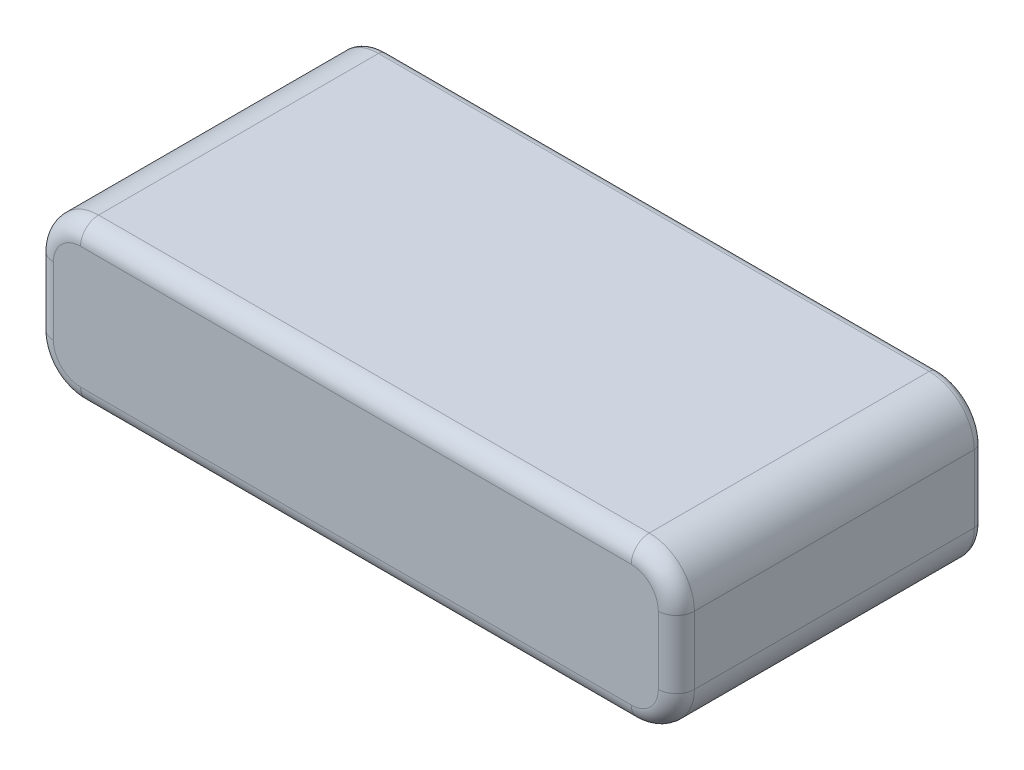
SolidWorks part; units mm, degrees
ref_plane "Front Plane" through (0, 0, 0) normal (0, 0, 1) x (1, 0, 0)
ref_plane "Top Plane" through (0, 0, 0) normal (0, 1, 0) x (1, 0, 0)
ref_plane "Right Plane" through (0, 0, 0) normal (1, 0, 0) x (0, 0, -1)
sketch "Sketch1" plane through (0, 0, 0) normal (0, 1, 0) x (1, 0, 0)
  line L1 (35.5, -17) -> (-35.5, -17)
  line L2 (35.5, -17) -> (35.5, 17)
  line L3 (35.5, 17) -> (-35.5, 17)
  line L4 (-35.5, -17) -> (-35.5, 17)
  line L5 (35.5, -17) -> (-35.5, 17) construction
  line L6 (35.5, 17) -> (-35.5, -17) construction
  point P0 (0, 0)
  dimension "D1" = 71
  dimension "D2" = 34
extrude "Boss-Extrude1" add sketch "Sketch1" along normal blind 17.5
fillet "Fillet1" radius 5 4 edges at (-35.5, 0, 0) (35.5, 0, 0) (35.5, 17.5, 0) (-35.5, 17.5, 0)
fillet "Fillet2" radius 2 8 edges at (-34.0355, 16.0355, 17) (0, 17.5, 17) (34.0355, 16.0355, 17) (35.5, 8.75, 17) (34.0355, 1.4645, 17) (0, 0, 17) (-34.0355, 1.4645, 17) (-35.5, 8.75, 17)
fillet "Fillet3" radius 1 8 edges at (34.0355, 1.4645, -17) (35.5, 8.75, -17) (34.0355, 16.0355, -17) (0, 17.5, -17) (-34.0355, 16.0355, -17) (-35.5, 8.75, -17) (-34.0355, 1.4645, -17) (0, 0, -17)
